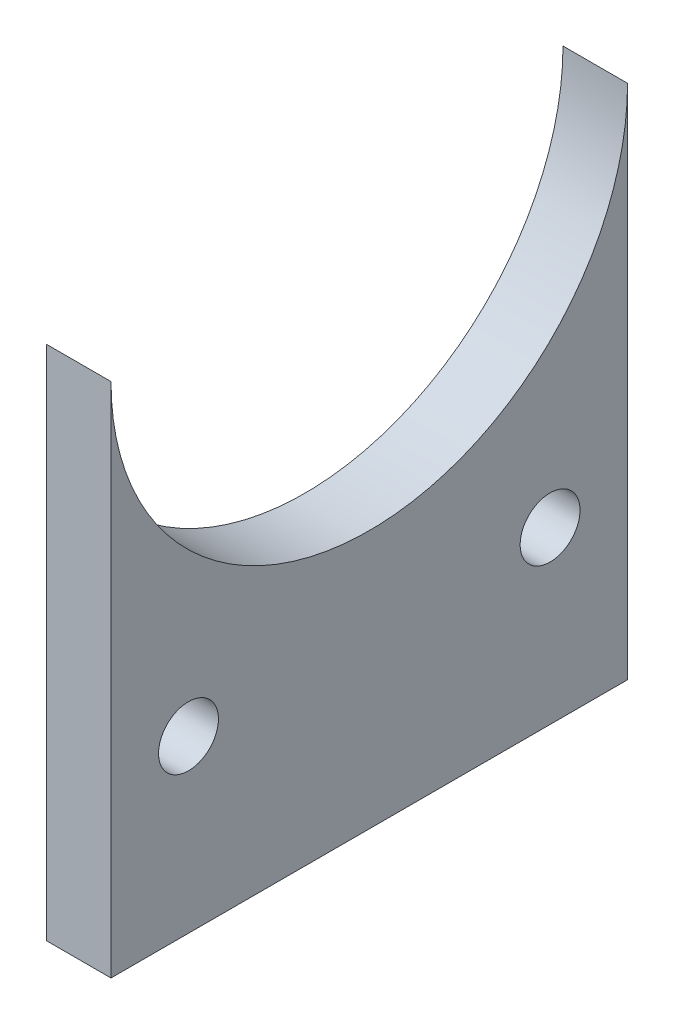
SolidWorks part; units mm, degrees
ref_plane "Front Plane" through (0, 0, 0) normal (0, 0, 1) x (1, 0, 0)
ref_plane "Top Plane" through (0, 0, 0) normal (0, 1, 0) x (1, 0, 0)
ref_plane "Right Plane" through (0, 0, 0) normal (1, 0, 0) x (0, 0, -1)
sketch "Sketch1" plane through (0, 0, 0) normal (1, 0, 0) x (0, 0, -1)
  line L1 (-12.7, -12.7) -> (12.7, -12.7)
  line L2 (-12.7, -12.7) -> (-12.7, 12.7)
  line L4 (12.7, -12.7) -> (12.7, 12.7)
  line L5 (-12.7, -12.7) -> (12.7, 12.7) construction
  line L6 (-12.7, 12.7) -> (12.7, -12.7) construction
  line L7 (-12.7, 12.7) -> (12.7, 12.7) construction
  arc A0 (-12.7, 12.7) -> (12.7, 12.7) centre (0, 12.7) ccw
  point P0 (0, 0)
  dimension "D1" = 25.4
  dimension "D3" = 25.4
extrude "Boss-Extrude1" add sketch "Sketch1" along normal blind 3.175
sketch "Sketch6" plane through (0, 0, 0) normal (-1, 0, 0) x (0, 0, 1)
  circle A0 centre (-8.8899, -4.309) radius 1.4732
extrude "Cut-Extrude2" cut sketch "Sketch6" against normal through all both and the other way through all
mirror "Mirror2" about plane through (0, 0, 0) normal (0, 0, 1) of "Cut-Extrude2"
